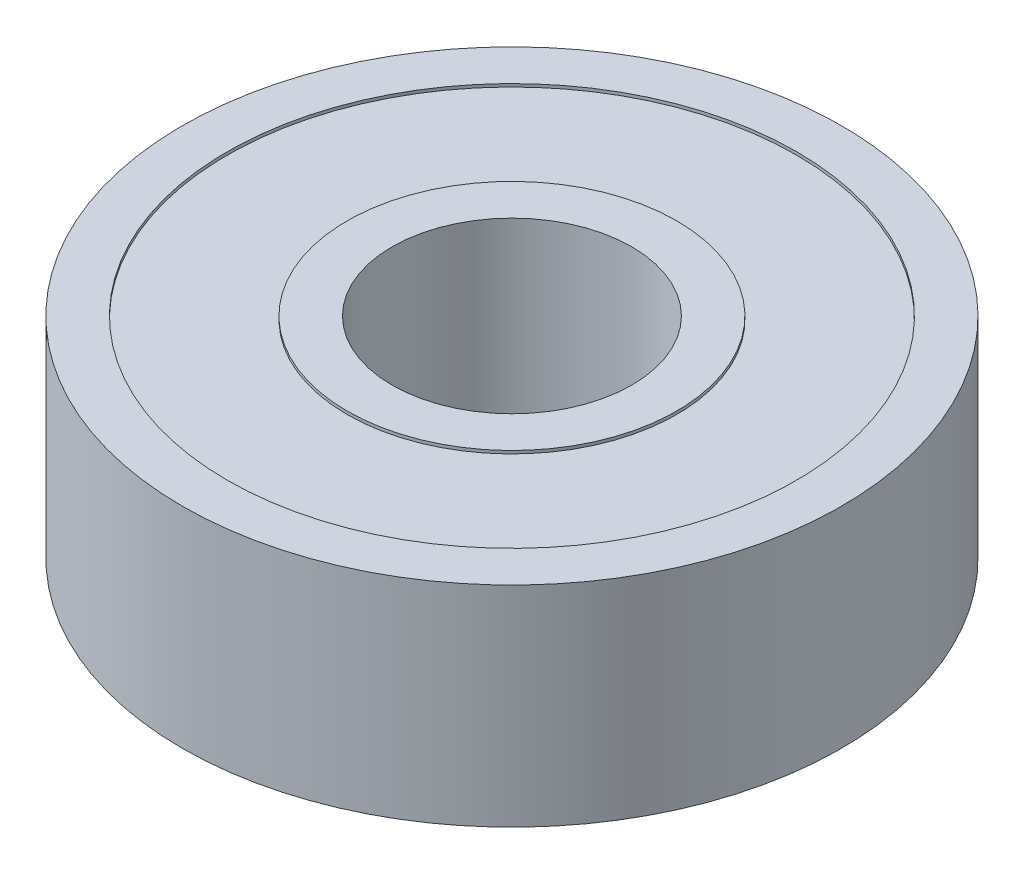
SolidWorks part; units mm, degrees
material "AISI 304"
ref_plane "Front Plane" through (0, 0, 0) normal (0, 0, 1) x (1, 0, 0)
ref_plane "Top Plane" through (0, 0, 0) normal (0, 1, 0) x (1, 0, 0)
ref_plane "Right Plane" through (0, 0, 0) normal (1, 0, 0) x (0, 0, -1)
sketch "Sketch1" plane through (0, 0, 0) normal (0, 1, 0) x (1, 0, 0)
  circle A0 centre (0, 0) radius 11
  circle A3 centre (0, 0) radius 4
  dimension "D1" = 22
  dimension "D4" = 8
extrude "Boss-Extrude1" add sketch "Sketch1" along normal blind 7
sketch "Sketch2" plane through (0, 7, 0) normal (0, 1, 0) x (1, 0, 0)
  circle A0 centre (0, 0) radius 9.5
  circle A1 centre (0, 0) radius 5.5
  circle A2 centre (0, 0) radius 11 construction
  circle A3 centre (0, 0) radius 4 construction
  dimension "D1" = 1.5
  dimension "D2" = 1.5
extrude "Cut-Extrude1" cut sketch "Sketch2" against normal blind 0.1
sketch "Sketch3" plane through (0, 0, 0) normal (0, -1, 0) x (1, 0, 0)
  circle A0 centre (0, 0) radius 9.5
  circle A1 centre (0, 0) radius 5.5
  circle A2 centre (0, 0) radius 11 construction
  circle A3 centre (0, 0) radius 4 construction
  dimension "D1" = 1.5
  dimension "D2" = 1.5
extrude "Cut-Extrude2" cut sketch "Sketch3" against normal blind 0.1
